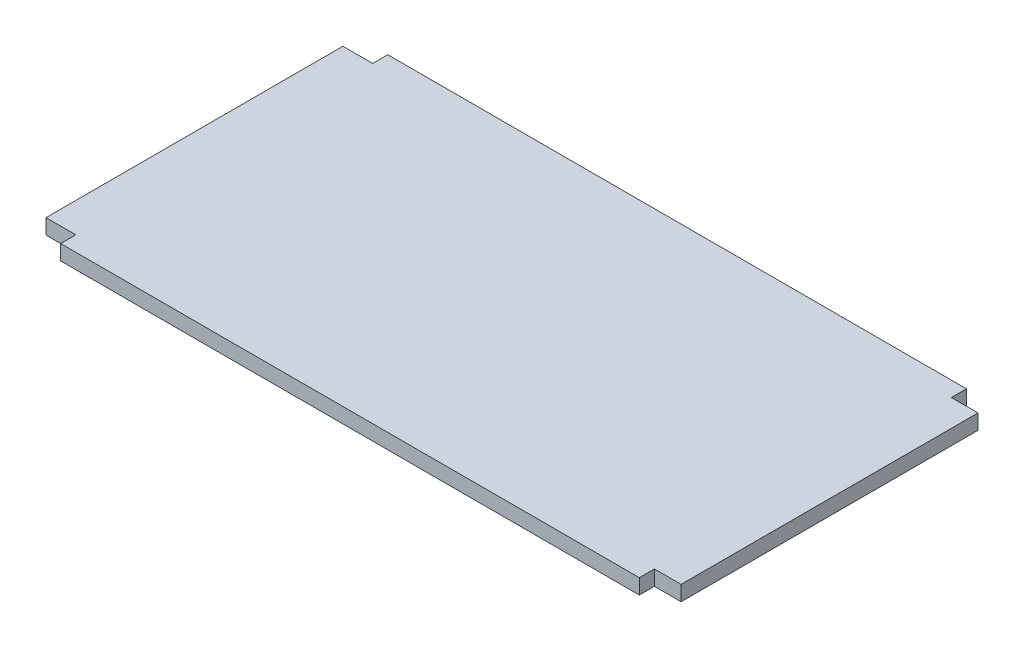
SolidWorks part; units mm, degrees
ref_plane "Front Plane" through (0, 0, 0) normal (0, 0, 1) x (1, 0, 0)
ref_plane "Top Plane" through (0, 0, 0) normal (0, 1, 0) x (1, 0, 0)
ref_plane "Right Plane" through (0, 0, 0) normal (1, 0, 0) x (0, 0, -1)
sketch "Sketch1" plane through (0, 0, 0) normal (0, 1, 0) x (1, 0, 0)
  line L0 (-57.5, 29.5) -> (-63.418, 29.5)
  line L1 (-57.5, 32.5) -> (57.5, 32.5)
  line L2 (-57.5, 32.5) -> (-57.5, 29.5)
  line L3 (-57.5, -32.5) -> (57.5, -32.5)
  line L4 (57.5, 32.5) -> (57.5, 29.5)
  line L5 (-57.5, 32.5) -> (57.5, -32.5) construction
  line L6 (-57.5, -32.5) -> (57.5, 32.5) construction
  line L7 (-63.418, 29.5) -> (-63.418, -29.5)
  line L8 (-63.418, -29.5) -> (-57.5, -29.5)
  line L9 (-57.5, -29.5) -> (-57.5, -32.5)
  line L10 (57.5, 29.5) -> (62.806, 29.5)
  line L11 (62.806, 29.5) -> (62.806, -29.5)
  line L12 (62.806, -29.5) -> (57.5, -29.5)
  line L13 (57.5, -29.5) -> (57.5, -32.5)
  point P0 (0, 0)
  dimension "D1" = 59
  dimension "D2" = 115
  dimension "D3" = 3
  dimension "D4" = 3
  dimension "D5" = 5.918
  dimension "D6" = 3
  dimension "D7" = 3
  dimension "D8" = 5.306
extrude "Boss-Extrude1" add sketch "Sketch1" against normal blind 3
